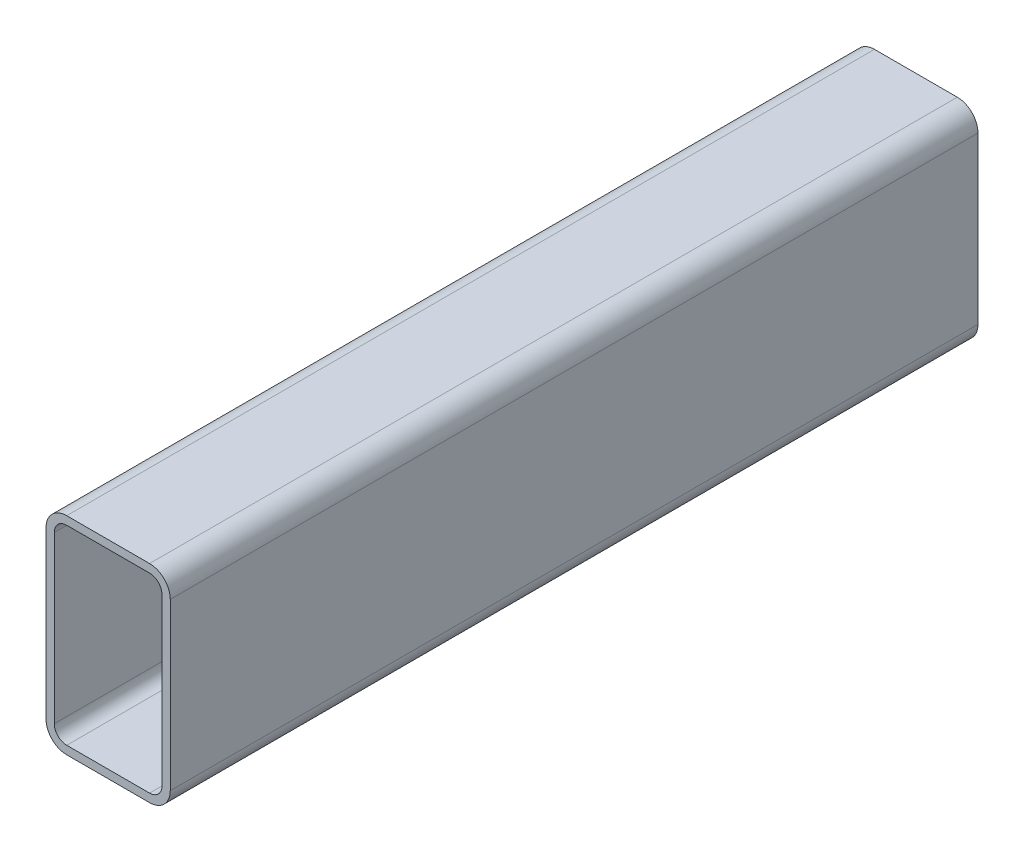
SolidWorks part; units mm, degrees
material "Plain Carbon Steel"
ref_plane "Front Plane" through (0, 0, 0) normal (0, 0, 1) x (1, 0, 0)
ref_plane "Top Plane" through (0, 0, 0) normal (0, 1, 0) x (1, 0, 0)
ref_plane "Right Plane" through (0, 0, 0) normal (1, 0, 0) x (0, 0, -1)
sketch "Sketch1" plane through (0, 0, 0) normal (0, 0, 1) x (1, 0, 0)
  line L0 (0, 73.7462) -> (0, -75.1353) construction
  line L1 (-89.5999, 0) -> (92.4117, 0) construction
  line L2 (-37.5, 0) -> (-37.5, -50)
  line L3 (-25, -62.5) -> (0, -62.5)
  line L4 (-32.5, 0) -> (-32.5, -50)
  line L5 (-25, -57.5) -> (0, -57.5)
  line L6 (-25, 57.5) -> (25, 57.5)
  line L7 (-32.5, 0) -> (-32.5, 50)
  line L8 (-25, 62.5) -> (25, 62.5)
  line L9 (-37.5, 0) -> (-37.5, 50)
  line L10 (25, -57.5) -> (0, -57.5)
  line L11 (32.5, 0) -> (32.5, -50)
  line L12 (32.5, 0) -> (32.5, 50)
  line L13 (25, -62.5) -> (0, -62.5)
  line L14 (37.5, 0) -> (37.5, -50)
  line L15 (37.5, 0) -> (37.5, 50)
  arc A0 (-37.5, -50) -> (-25, -62.5) centre (-25, -50) ccw
  arc A1 (-32.5, -50) -> (-25, -57.5) centre (-25, -50) ccw
  arc A2 (-32.5, 50) -> (-25, 57.5) centre (-25, 50) cw
  arc A3 (-37.5, 50) -> (-25, 62.5) centre (-25, 50) cw
  arc A4 (32.5, -50) -> (25, -57.5) centre (25, -50) cw
  arc A5 (32.5, 50) -> (25, 57.5) centre (25, 50) ccw
  arc A6 (37.5, -50) -> (25, -62.5) centre (25, -50) cw
  arc A7 (37.5, 50) -> (25, 62.5) centre (25, 50) ccw
  point P10 (-37.5, -62.5)
  point P31 (0, 57.5)
  point P37 (0, 62.5)
  dimension "D3" = 12.5
  dimension "D1" = 62.5
  dimension "D2" = 37.5
  dimension "D4" = 5
extrude "Boss-Extrude1" add sketch "Sketch1" along normal mid plane 487.5
